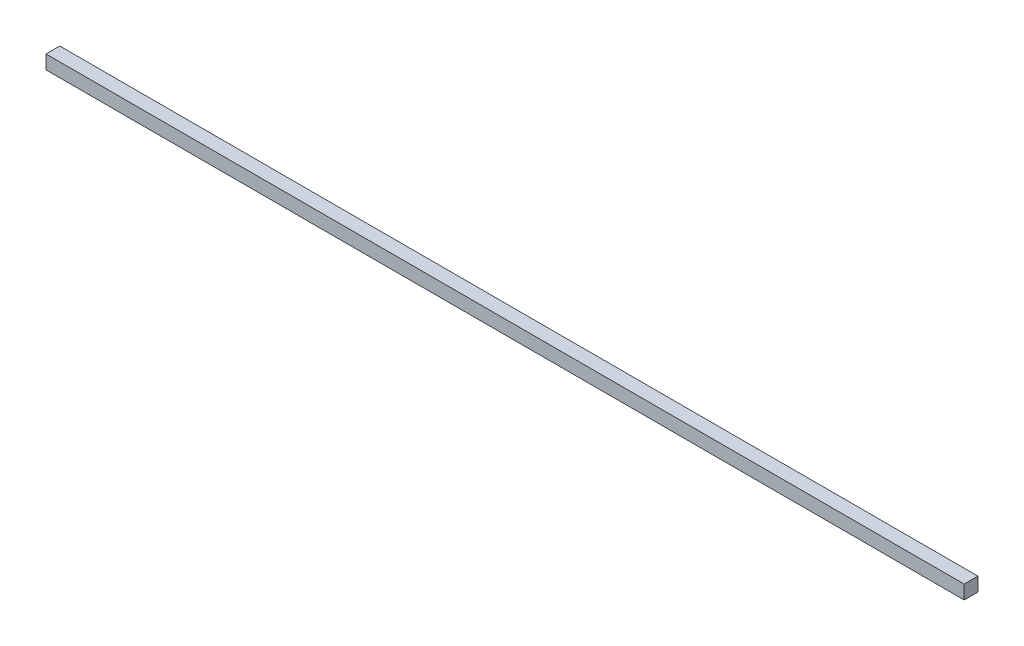
SolidWorks part; units mm, degrees
material "Pine"
ref_plane "Piano frontale" through (0, 0, 0) normal (0, 0, 1) x (1, 0, 0)
ref_plane "Piano superiore" through (0, 0, 0) normal (0, 1, 0) x (1, 0, 0)
ref_plane "Piano destro" through (0, 0, 0) normal (1, 0, 0) x (0, 0, -1)
sketch "Sketch1" plane through (0, 0, 0) normal (0, 0, 1) x (1, 0, 0)
  line L1 (0, 0) -> (100, 0)
  line L2 (0, 0) -> (0, 1.5)
  line L3 (0, 1.5) -> (100, 1.5)
  line L4 (100, 0) -> (100, 1.5)
  dimension "D1" = 100
  dimension "D2" = 1.5
extrude "Boss-Extrude1" add sketch "Sketch1" along normal blind 1.5
scale "Scale1" scale about origin uniform scaling yes scale factor 10
